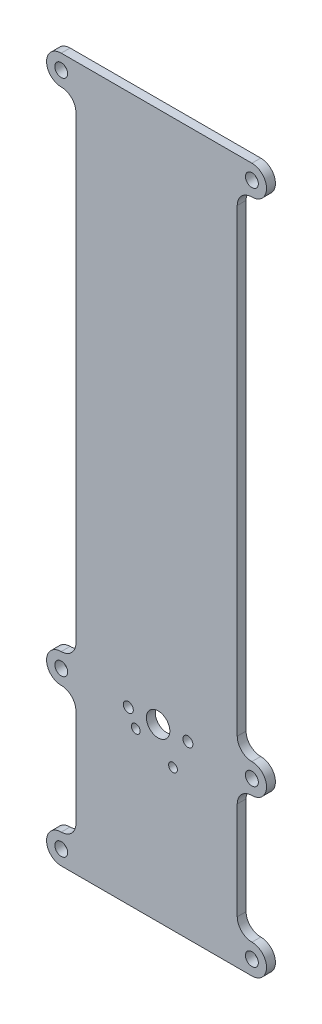
SolidWorks part; units mm, degrees
ref_plane "Front Plane" through (0, 0, 0) normal (0, 0, 1) x (1, 0, 0)
ref_plane "Top Plane" through (0, 0, 0) normal (0, 1, 0) x (1, 0, 0)
ref_plane "Right Plane" through (0, 0, 0) normal (1, 0, 0) x (0, 0, -1)
sketch "Sketch1" plane through (0, 0, 0) normal (0, 0, 1) x (1, 0, 0)
  line L6 (136.512, -46.6938) -> (104.012, -46.6938)
  line L7 (106.512, -54.1938) -> (106.512, -132.541)
  line L8 (106.512, -142.541) -> (106.512, -159.1938)
  line L9 (104.012, -166.6938) -> (136.512, -166.6938)
  line L10 (134.012, -159.1938) -> (134.012, -142.541)
  line L11 (134.012, -132.541) -> (134.012, -54.1938)
  line L12 (136.512, -46.6938) -> (104.012, -46.6938)
  line L13 (106.512, -54.1938) -> (106.512, -132.541)
  line L14 (106.512, -142.541) -> (106.512, -159.1938)
  line L15 (104.012, -166.6938) -> (136.512, -166.6938)
  line L16 (134.012, -159.1938) -> (134.012, -142.541)
  line L17 (134.012, -132.541) -> (134.012, -54.1938)
  circle A1 centre (125.603, -137.541) radius 0.85
  circle A2 centre (125.603, -137.541) radius 0.85
  circle A3 centre (120.523, -137.541) radius 2
  circle A4 centre (120.523, -137.541) radius 2
  circle A5 centre (115.443, -137.541) radius 0.85
  circle A6 centre (115.443, -137.541) radius 0.85
  circle A7 centre (116.713, -140.081) radius 0.75
  circle A8 centre (116.713, -140.081) radius 0.75
  circle A9 centre (123.063, -142.621) radius 0.75
  circle A10 centre (123.063, -142.621) radius 0.75
  circle A11 centre (104.012, -137.541) radius 1.1
  circle A12 centre (104.012, -137.541) radius 1.1
  circle A13 centre (104.012, -164.1938) radius 1.1
  arc A14 (136.512, -51.6938) -> (136.512, -46.6938) centre (136.512, -49.1938) ccw
  arc A15 (104.012, -46.6938) -> (104.012, -51.6938) centre (104.012, -49.1938) ccw
  arc A16 (106.512, -54.1938) -> (104.012, -51.6938) centre (104.012, -54.1938) ccw
  arc A17 (104.012, -135.041) -> (106.512, -132.541) centre (104.012, -132.541) ccw
  arc A18 (104.012, -135.041) -> (104.012, -140.041) centre (104.012, -137.541) ccw
  arc A19 (106.512, -142.541) -> (104.012, -140.041) centre (104.012, -142.541) ccw
  arc A20 (104.012, -161.6938) -> (106.512, -159.1938) centre (104.012, -159.1938) ccw
  arc A21 (104.012, -161.6938) -> (104.012, -166.6938) centre (104.012, -164.1938) ccw
  arc A22 (136.512, -166.6938) -> (136.512, -161.6938) centre (136.512, -164.1938) ccw
  arc A23 (134.012, -159.1938) -> (136.512, -161.6938) centre (136.512, -159.1938) ccw
  arc A24 (136.512, -140.041) -> (134.012, -142.541) centre (136.512, -142.541) ccw
  arc A25 (136.512, -140.041) -> (136.512, -135.041) centre (136.512, -137.541) ccw
  arc A26 (134.012, -132.541) -> (136.512, -135.041) centre (136.512, -132.541) ccw
  arc A27 (136.512, -51.6938) -> (134.012, -54.1938) centre (136.512, -54.1938) ccw
  arc A28 (136.512, -51.6938) -> (136.512, -46.6938) centre (136.512, -49.1938) ccw
  arc A29 (104.012, -46.6938) -> (104.012, -51.6938) centre (104.012, -49.1938) ccw
  arc A30 (106.512, -54.1938) -> (104.012, -51.6938) centre (104.012, -54.1938) ccw
  arc A31 (104.012, -135.041) -> (106.512, -132.541) centre (104.012, -132.541) ccw
  arc A32 (104.012, -135.041) -> (104.012, -140.041) centre (104.012, -137.541) ccw
  arc A33 (106.512, -142.541) -> (104.012, -140.041) centre (104.012, -142.541) ccw
  arc A34 (104.012, -161.6938) -> (106.512, -159.1938) centre (104.012, -159.1938) ccw
  arc A35 (104.012, -161.6938) -> (104.012, -166.6938) centre (104.012, -164.1938) ccw
  arc A36 (136.512, -166.6938) -> (136.512, -161.6938) centre (136.512, -164.1938) ccw
  arc A37 (134.012, -159.1938) -> (136.512, -161.6938) centre (136.512, -159.1938) ccw
  arc A38 (136.512, -140.041) -> (134.012, -142.541) centre (136.512, -142.541) ccw
  arc A39 (136.512, -140.041) -> (136.512, -135.041) centre (136.512, -137.541) ccw
  arc A40 (134.012, -132.541) -> (136.512, -135.041) centre (136.512, -132.541) ccw
  arc A41 (136.512, -51.6938) -> (134.012, -54.1938) centre (136.512, -54.1938) ccw
  circle A42 centre (104.012, -164.1938) radius 1.1
  circle A43 centre (136.512, -164.1938) radius 1.1
  circle A44 centre (136.512, -164.1938) radius 1.1
  circle A45 centre (136.512, -137.541) radius 1.1
  circle A46 centre (136.512, -137.541) radius 1.1
  circle A47 centre (136.512, -49.1938) radius 1.1
  circle A48 centre (136.512, -49.1938) radius 1.1
  circle A49 centre (104.012, -49.1938) radius 1.1
  circle A50 centre (104.012, -49.1938) radius 1.1
  dimension "D1" = 0
  dimension "D2" = 0
  dimension "D3" = 0
  dimension "D4" = 0
  dimension "D5" = 0
  dimension "D6" = 0
  dimension "D7" = 0
  dimension "D8" = 0
  dimension "D9" = 0
  dimension "D10" = 0
  dimension "D11" = 0
  dimension "D12" = 0
extrude "Boss-Extrude1" add sketch "Sketch1" against normal up to surface (1.51 mm away)
